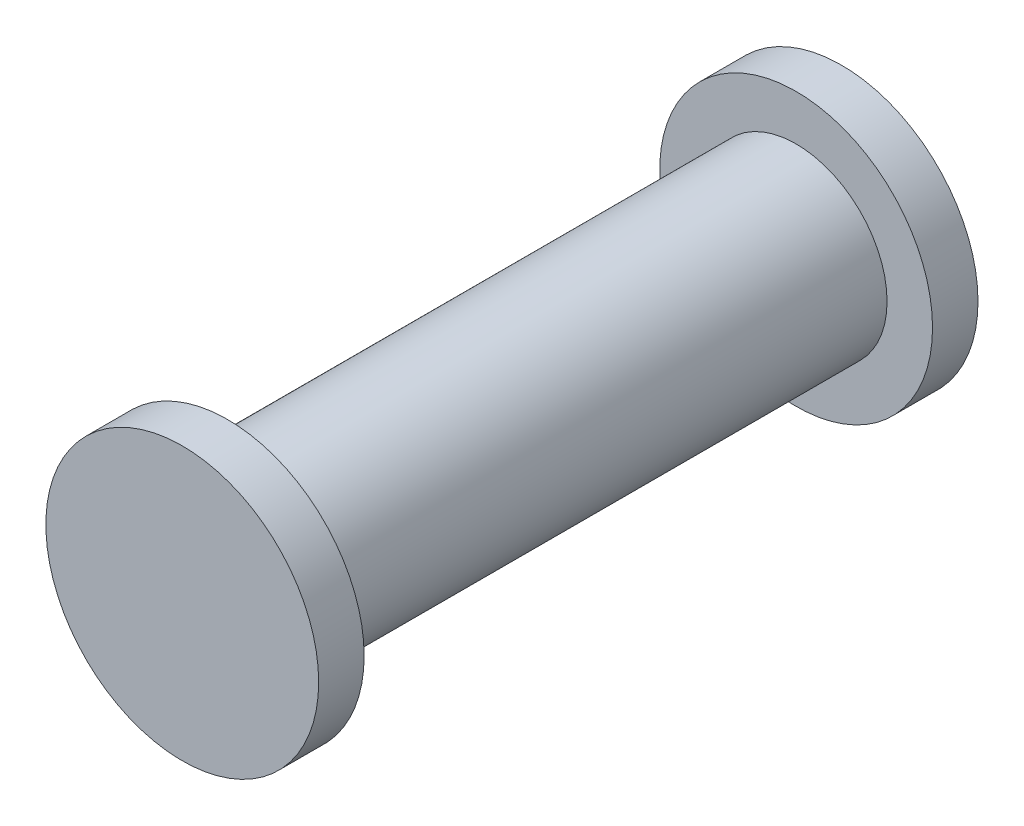
SolidWorks part; units mm, degrees
ref_plane "Alzado" through (0, 0, 0) normal (0, 0, 1) x (1, 0, 0)
ref_plane "Planta" through (0, 0, 0) normal (0, 1, 0) x (1, 0, 0)
ref_plane "Vista lateral" through (0, 0, 0) normal (1, 0, 0) x (0, 0, -1)
sketch "Croquis1" plane through (0, 0, 0) normal (0, 0, 1) x (1, 0, 0)
  circle A0 centre (0, 0) radius 4
  dimension "D1" = 8
extrude "Saliente-Extruir1" add sketch "Croquis1" along normal mid plane 25
sketch "Croquis2" plane through (0, 0, 12.5) normal (0, 0, 1) x (1, 0, 0)
  circle A0 centre (0, 0) radius 6
  dimension "D1" = 12
extrude "Saliente-Extruir2" add sketch "Croquis2" along normal blind 2
mirror "Simetría1" about plane through (0, 0, 0) normal (0, 0, 1) of "Saliente-Extruir2"
